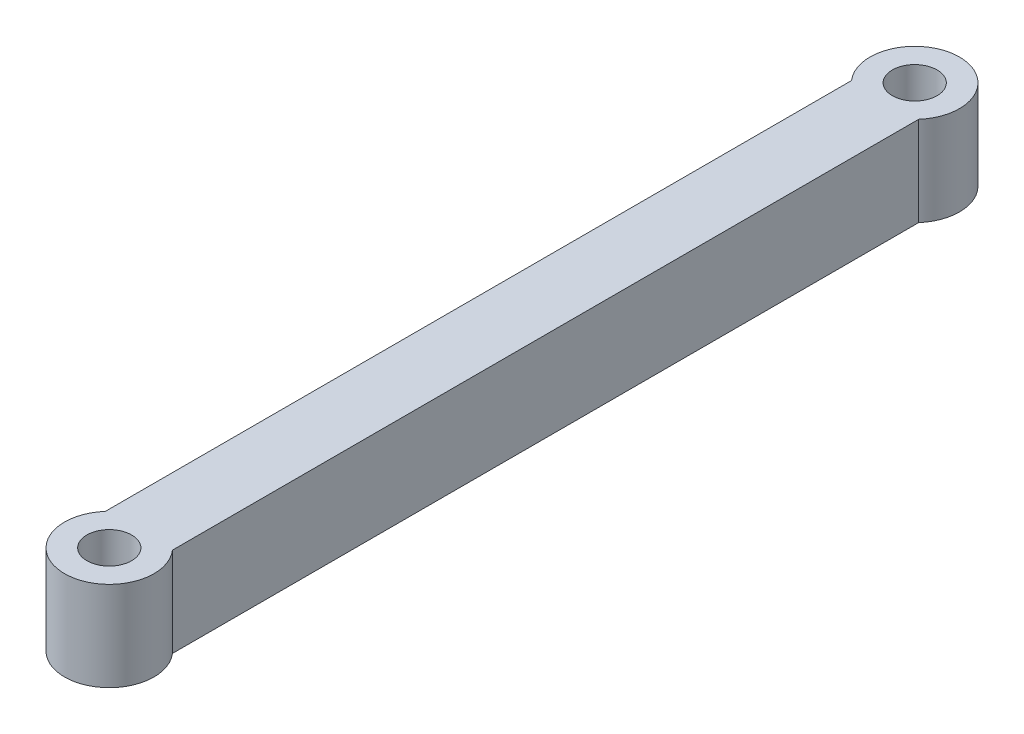
SolidWorks part; units mm, degrees
ref_plane "Front Plane" through (0, 0, 0) normal (0, 0, 1) x (1, 0, 0)
ref_plane "Top Plane" through (0, 0, 0) normal (0, 1, 0) x (1, 0, 0)
ref_plane "Right Plane" through (0, 0, 0) normal (1, 0, 0) x (0, 0, -1)
sketch "Sketch1" plane through (0, 0, 0) normal (0, 1, 0) x (1, 0, 0)
  line L0 (-15.5294, 0) -> (16.7059, 0) construction
  line L2 (-3.75, 41.6928) -> (-3.75, -41.6928)
  line L4 (3.75, 41.6928) -> (3.75, -41.6928)
  arc A0 (3.75, 41.6928) -> (-3.75, 41.6928) centre (0, 45) ccw
  arc A1 (3.75, -41.6928) -> (-3.75, -41.6928) centre (0, -45) cw
  circle A2 centre (0, 45) radius 2.5
  circle A3 centre (0, -45) radius 2.5
  point P0 (0, 0)
  dimension "D1" = 90
  dimension "D2" = 7.5
extrude "Boss-Extrude1" add sketch "Sketch1" along normal blind 10
